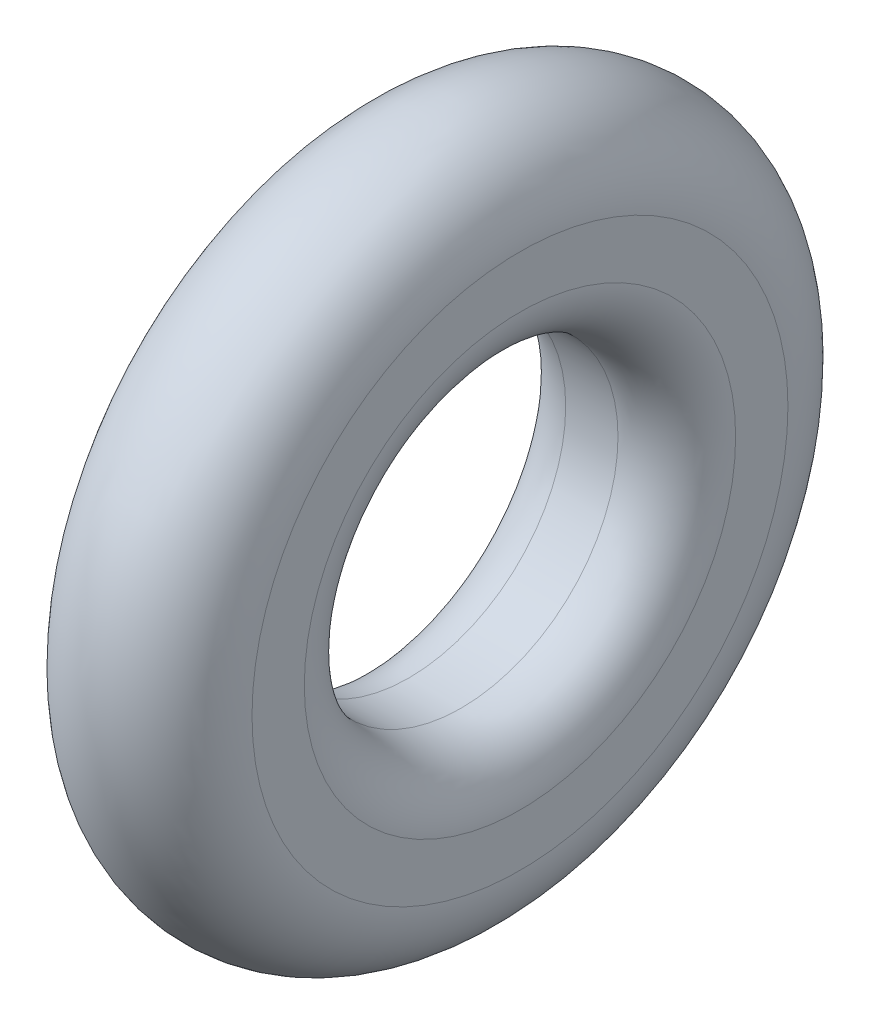
SolidWorks part; units mm, degrees
ref_plane "Front Plane" through (0, 0, 0) normal (0, 0, 1) x (1, 0, 0)
ref_plane "Top Plane" through (0, 0, 0) normal (0, 1, 0) x (1, 0, 0)
ref_plane "Right Plane" through (0, 0, 0) normal (1, 0, 0) x (0, 0, -1)
sketch "Sketch1" plane through (0, 0, 0) normal (0, 0, 1) x (1, 0, 0)
  line L0 (0, 0) -> (0, 2.1996) construction
  line L1 (0, 0) -> (-2.1476, 0) construction
  line L2 (-0.5, 3) -> (0.5, 3)
  line L3 (1.625, 4.125) -> (1.625, 5.125)
  line L4 (-1.625, 4.125) -> (-1.625, 5.125)
  arc A0 (0.5, 3) -> (1.625, 4.125) centre (0.5, 4.125) ccw
  arc A1 (-0.5, 3) -> (-1.625, 4.125) centre (-0.5, 4.125) cw
  arc A3 (-1.625, 5.125) -> (1.625, 5.125) centre (0, 5.125) cw
  point P13 (0, 6.75)
  point P14 (0.1363, 1.3835)
  point P15 (0, 0)
  point P16 (-0.3916, 6.75)
  point P17 (1.293, 4.7701)
  point P18 (0, 3)
  point P19 (0, 6.75)
  point P20 (0.5, 3.1778)
  dimension "D1" = 1
  dimension "D2" = 1
  dimension "D3" = 1
  dimension "D5" = 6.75
  dimension "D6" = 3
revolve "Revolve1" add sketch "Sketch1" angle 360 about L1
